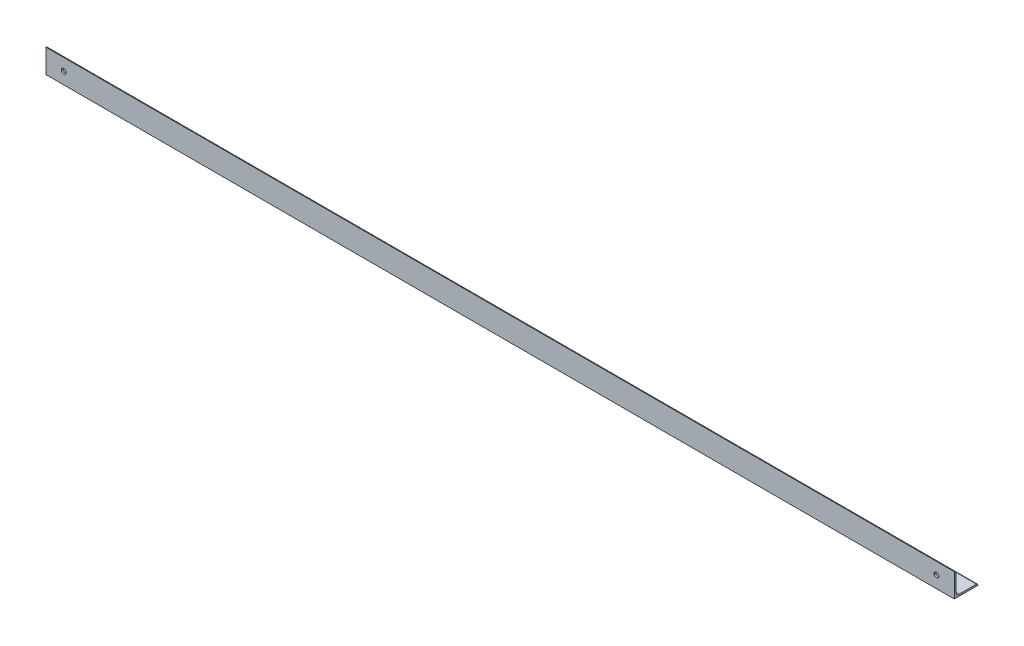
SolidWorks part; units mm, degrees
ref_plane "Front Plane" through (0, 0, 0) normal (0, 0, 1) x (1, 0, 0)
ref_plane "Top Plane" through (0, 0, 0) normal (0, 1, 0) x (1, 0, 0)
ref_plane "Right Plane" through (0, 0, 0) normal (1, 0, 0) x (0, 0, -1)
sketch "Sketch1" plane through (0, 0, 0) normal (0, 1, 0) x (1, 0, 0)
  line L0 (0, 0) -> (1530, 0)
  dimension "D1" = 1530
other "L angle (equal) 40X40X3(5)"
ref_plane "Plane1" through (0, 0, 0) normal (1, 0, 0) x (0, 0, -1)
sketch "Sketch13" plane through (0, 0, 0) normal (1, 0, 0) x (0, 0, -1)
  line L0 (0, 40) -> (0, 0)
  line L2 (3, 37) -> (3, 9)
  line L3 (9, 3) -> (37, 3)
  line L5 (40, 0) -> (0, 0)
  arc A0 (3, 37) -> (0, 40) centre (0, 37) ccw
  arc A1 (40, 0) -> (37, 3) centre (37, 0) ccw
  arc A2 (9, 3) -> (3, 9) centre (9, 9) cw
  point P8 (0, 20)
  point P9 (20, 0)
  point P10 (0, 0)
  dimension "Radius_2" = 3
  dimension "Radius_1" = 6
  dimension "V_leg" = 40
  dimension "H_leg" = 40
  dimension "thickness" = 3
ref_plane "Plane2" through (0, 0, 0) normal (0, 0, 1) x (1, 0, 0)
sketch "Sketch16" plane through (0, 0, 0) normal (0, 0, 1) x (1, 0, 0)
  line L0 (0, 40) -> (0, 0) construction
  line L1 (1530, 40) -> (1530, 0) construction
  line L3 (30, 40) -> (30, 0) construction
  line L5 (1500, 40) -> (1500, 0) construction
  circle A0 centre (1500, 20) radius 4
  circle A1 centre (30, 20) radius 4
  dimension "D1" = 30
  dimension "D2" = 30
extrude "Cut-Extrude1" cut sketch "Sketch16" against normal through all
